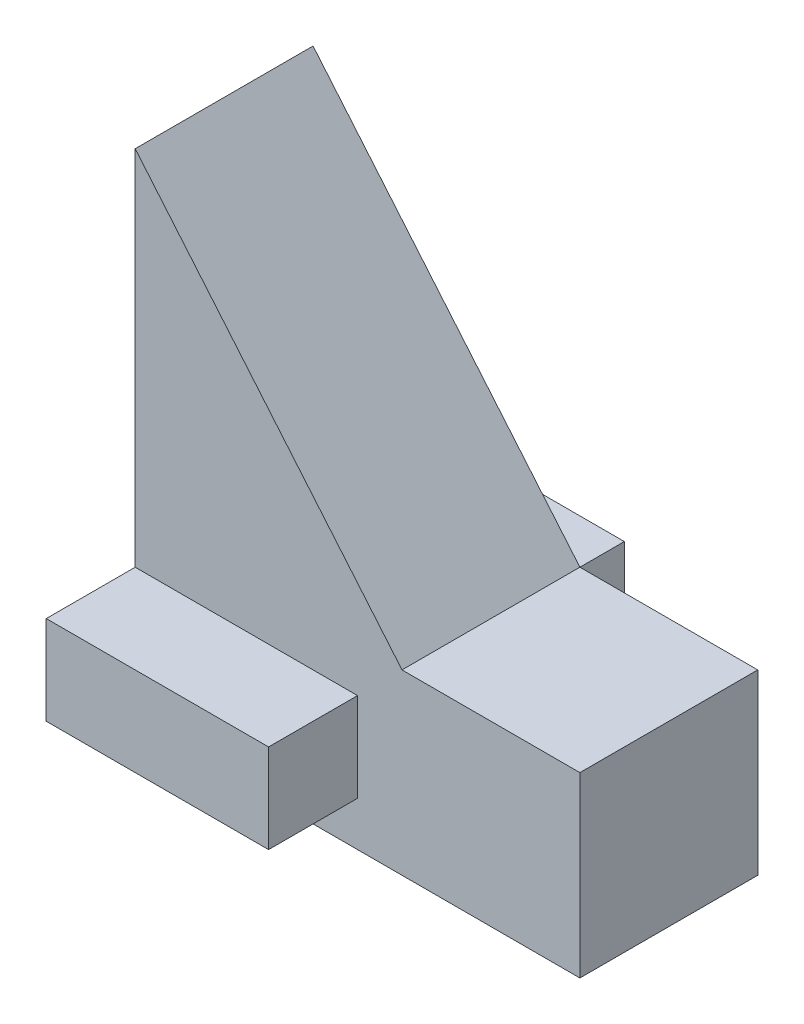
SolidWorks part; units mm, degrees
ref_plane "Plan de face" through (0, 0, 0) normal (0, 0, 1) x (1, 0, 0)
ref_plane "Plan de dessus" through (0, 0, 0) normal (0, 1, 0) x (1, 0, 0)
ref_plane "Plan de droite" through (0, 0, 0) normal (1, 0, 0) x (0, 0, -1)
sketch "Esquisse1" plane through (0, 0, 0) normal (0, 0, 1) x (1, 0, 0)
  line L0 (21.6104, -2.991) -> (25.6104, -2.991)
  line L1 (25.6104, -2.991) -> (25.6104, -6.991)
  line L2 (25.6104, -6.991) -> (15.6104, -6.991)
  line L3 (15.6104, -6.991) -> (15.6104, 4.1595)
  line L4 (15.6104, 4.1595) -> (21.6104, -2.991)
  line L5 (23.6104, 11.709) -> (23.6104, -8.691) construction
  line L6 (13.9314, -4.991) -> (15.2514, -4.991) construction
  line L7 (22.0604, -10.991) -> (10.0604, -10.991) construction
  point P7 (25.6104, -4.991)
  dimension "D1" = 2
  dimension "D2" = 4
  dimension "D3" = 10
  dimension "D4" = 40
  dimension "D5" = 4
  dimension "D6" = 4
extrude "Boss.-Extru.1" add sketch "Esquisse1" along normal blind 4
sketch "Esquisse2" plane through (0, 0, 4) normal (0, 0, 1) x (1, 0, 0)
  line L0 (20.6104, -3.991) -> (15.6104, -3.991)
  line L2 (15.6104, 4.1595) -> (15.6104, -6.991) construction
  line L3 (15.6104, -3.991) -> (15.6104, -5.991)
  line L4 (15.6104, -5.991) -> (20.6104, -5.991)
  line L5 (20.6104, -5.991) -> (20.6104, -3.991)
  line L6 (25.6104, -6.991) -> (25.6104, -2.991) construction
  line L7 (15.6104, -6.991) -> (25.6104, -6.991) construction
  point P2 (25.6104, -4.991)
  point P9 (20.6104, -4.991)
  point P13 (20.6104, -6.991)
  dimension "D1" = 2
extrude "Boss.-Extru.2" add sketch "Esquisse2" along normal blind 2
ref_plane "Plan1" through (0, 0, 2) normal (0, 0, 1) x (1, 0, 0)
mirror "Symétrie1" about plane through (0, 0, 2) normal (0, 0, 1) of "Boss.-Extru.2"
ref_plane "Plan2" through (0, -4.991, 0) normal (0, 1, 0) x (1, 0, 0)
